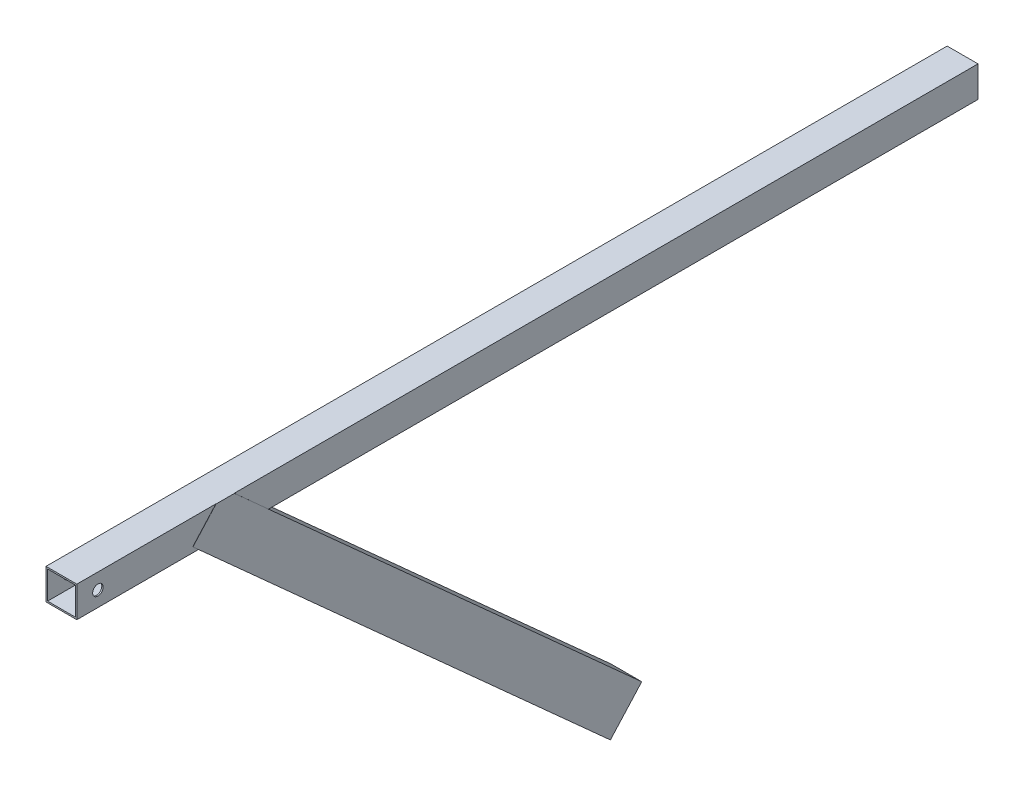
SolidWorks part; units mm, degrees
ref_plane "Front Plane" through (0, 0, 0) normal (0, 0, 1) x (1, 0, 0)
ref_plane "Top Plane" through (0, 0, 0) normal (0, 1, 0) x (1, 0, 0)
ref_plane "Right Plane" through (0, 0, 0) normal (1, 0, 0) x (0, 0, -1)
sketch "Sketch2" plane through (0, 0, 0) normal (0, 0, 1) x (1, 0, 0)
  line L1 (0, 0) -> (-26.3522, 0)
  line L2 (0, 0) -> (0, 26.3522)
  line L3 (0, 26.3522) -> (-26.3522, 26.3522)
  line L4 (-26.3522, 0) -> (-26.3522, 26.3522)
  line L5 (-1.1913, 1.2761) -> (-24.9913, 1.2761)
  line L6 (-1.1913, 1.2761) -> (-1.1913, 25.0761)
  line L7 (-1.1913, 25.0761) -> (-24.9913, 25.0761)
  line L8 (-24.9913, 1.2761) -> (-24.9913, 25.0761)
extrude "Boss-Extrude1" add sketch "Sketch2" along normal mid plane 770
ref_plane "Plane1" through (10, 0, 0) normal (1, 0, 0) x (0, 0, -1)
sketch "Sketch3" plane through (-26.3522, 0, 0) normal (-1, 0, 0) x (0, 0, 1)
  line L0 (385, 26.3522) -> (385, 0) construction
  circle A0 centre (367, 13) radius 4.5
  dimension "D1" = 9
  dimension "D2" = 18
extrude "Cut-Extrude1" cut sketch "Sketch3" against normal through all
ref_plane "Plane2" through (0, -176.9909, -196.5683) normal (0, 0.6691, 0.7431) x (1, 0, 0)
sketch "Sketch4" plane through (0, -176.9909, -196.5683) normal (0, 0.6691, 0.7431) x (1, 0, 0)
  line L0 (-24.9913, -256.667) -> (-1.1913, -256.667) construction
  line L1 (0.1695, -188.0462) -> (-26.3522, -188.0462)
  line L2 (0.1695, -188.0462) -> (0.1695, -148.0462)
  line L3 (0.1695, -148.0462) -> (-26.3522, -148.0462)
  line L4 (-26.3522, -188.0462) -> (-26.3522, -148.0462)
  line L5 (0.1695, -188.0462) -> (-26.3522, -148.0462) construction
  line L6 (0.1695, -148.0462) -> (-26.3522, -188.0462) construction
  line L7 (-26.3522, -238.0318) -> (-26.3522, 277.1988) construction
  line L9 (-3.1457, -183.0462) -> (-23.037, -183.0462)
  line L10 (-3.1457, -183.0462) -> (-3.1457, -153.0462)
  line L11 (-3.1457, -153.0462) -> (-23.037, -153.0462)
  line L12 (-23.037, -183.0462) -> (-23.037, -153.0462)
  line L13 (-3.1457, -183.0462) -> (-23.037, -153.0462) construction
  line L14 (-3.1457, -153.0462) -> (-23.037, -183.0462) construction
  point P0 (-13.0913, -168.0462)
  point P8 (-13.0913, -256.667)
  point P13 (-13.0913, -168.0462)
  dimension "D1" = 40
  dimension "D2" = 30
extrude "Boss-Extrude2" add sketch "Sketch4" along normal blind 480
sketch "Sketch5" plane through (-26.3522, 0, 0) normal (-1, 0, 0) x (0, 0, 1)
  line L0 (266.2444, 26.3522) -> (250.5186, 26.3522)
  line L1 (250.5186, 26.3522) -> (259.2034, 34.172)
  line L2 (259.2034, 34.172) -> (266.2444, 26.3522)
extrude "Cut-Extrude2" cut sketch "Sketch5" against normal through all
